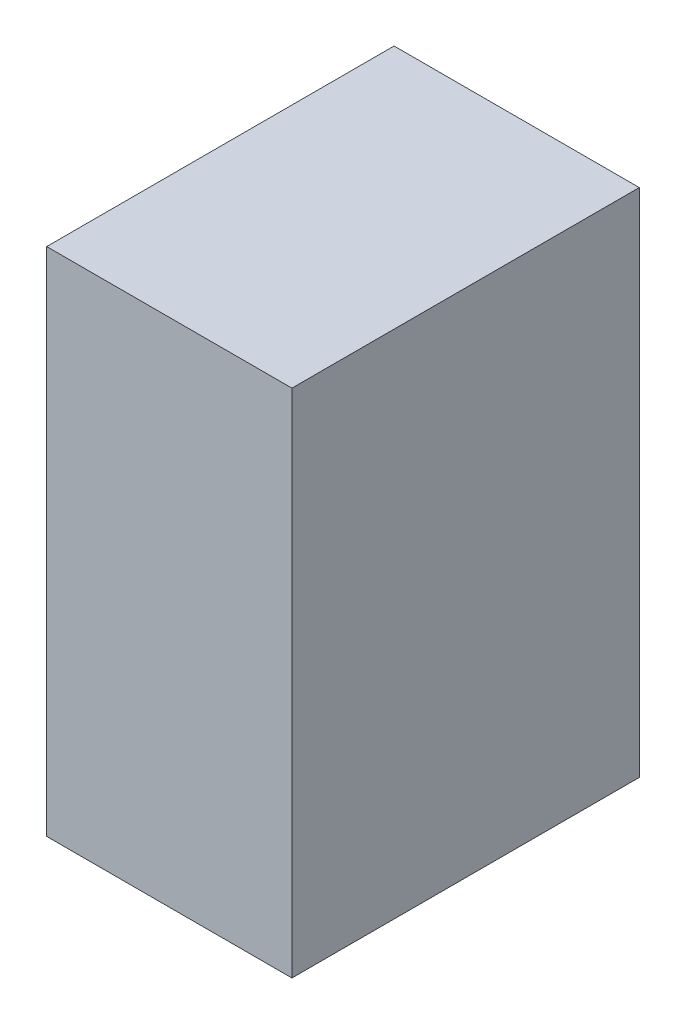
SolidWorks part; units mm, degrees
ref_plane "Plan de face" through (0, 0, 0) normal (0, 0, 1) x (1, 0, 0)
ref_plane "Plan de dessus" through (0, 0, 0) normal (0, 1, 0) x (1, 0, 0)
ref_plane "Plan de droite" through (0, 0, 0) normal (1, 0, 0) x (0, 0, -1)
sketch "Esquisse1" plane through (0, 0, 0) normal (0, 0, 1) x (1, 0, 0)
  line L1 (18, -37.5) -> (-18, -37.5)
  line L2 (18, -37.5) -> (18, 37.5)
  line L3 (18, 37.5) -> (-18, 37.5)
  line L4 (-18, -37.5) -> (-18, 37.5)
  line L5 (18, -37.5) -> (-18, 37.5) construction
  line L6 (18, 37.5) -> (-18, -37.5) construction
  point P0 (0, 0)
  dimension "D1" = 75
  dimension "D2" = 36
extrude "Boss.-Extru.1" add sketch "Esquisse1" along normal mid plane 51
